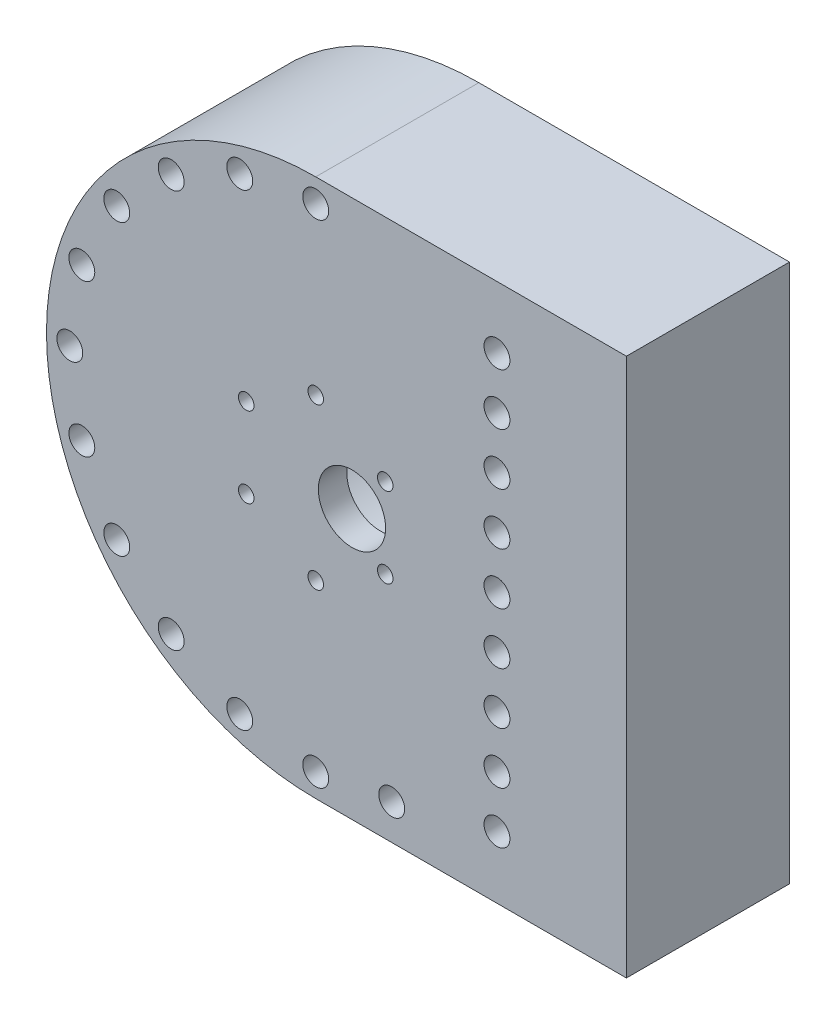
SolidWorks part; units mm, degrees
ref_plane "Alzado" through (0, 0, 0) normal (0, 0, 1) x (1, 0, 0)
ref_plane "Planta" through (0, 0, 0) normal (0, 1, 0) x (1, 0, 0)
ref_plane "Vista lateral" through (0, 0, 0) normal (1, 0, 0) x (0, 0, -1)
sketch "Croquis1" plane through (0, 0, 0) normal (0, 0, 1) x (1, 0, 0)
  line L0 (0, 52) -> (60, 52)
  line L1 (0, -52) -> (60, -52)
  line L2 (60, 52) -> (60, -52)
  arc A0 (0, 52) -> (0, -52) centre (0, 0) ccw
  circle A1 centre (0, 0) radius 18.725
  dimension "D1" = 104
  dimension "D3" = 37.45
  dimension "D2" = 60
extrude "Saliente-Extruir1" add sketch "Croquis1" along normal blind 26
sketch "Croquis2" plane through (0, 0, 26) normal (0, 0, 1) x (1, 0, 0)
  line L9 (0, -52) -> (60, -52)
  line L10 (60, -52) -> (60, 52)
  line L11 (60, 52) -> (0, 52)
  line L12 (0, -52) -> (60, -52)
  line L13 (60, -52) -> (60, 52)
  line L14 (60, 52) -> (0, 52)
  circle A0 centre (0, 0) radius 18.5 construction
  circle A3 centre (7, 0) radius 6.5
  circle A4 centre (13.4234, -7.75) radius 1.5
  circle A5 centre (13.4234, 7.75) radius 1.5
  circle A6 centre (0, 15.5) radius 1.5
  circle A7 centre (0, -15.5) radius 1.5
  circle A8 centre (-13.4234, -7.75) radius 1.5
  circle A9 centre (-13.4234, 7.75) radius 1.5
  arc A12 (0, 52) -> (0, -52) centre (0, 0) ccw
  arc A13 (0, 52) -> (0, -52) centre (0, 0) ccw
  dimension "D1" = 37
  dimension "D2" = 13
  dimension "D3" = 7
  dimension "D4" = 0
extrude "Saliente-Extruir2" add sketch "Croquis2" along normal blind 5.5
sketch "Croquis3" plane through (0, 0, 31.5) normal (0, 0, 1) x (1, 0, 0)
  line L0 (0, 0) -> (66.312, 0) construction
  line L1 (35, 40) -> (35, 20) construction
  line L2 (0, 0) -> (0, 47.5) construction
  line L3 (0, 0) -> (-14.6783, 45.1752) construction
  circle A0 centre (35, 0) radius 2.5
  circle A1 centre (35, 20) radius 2.5
  circle A2 centre (35, 40) radius 2.5
  circle A3 centre (35, -40) radius 2.5
  circle A4 centre (35, -20) radius 2.5
  circle A5 centre (0, 0) radius 47.5 construction
  circle A6 centre (-14.6783, 45.1752) radius 2.5
  circle A7 centre (-38.4283, 27.9198) radius 2.5
  circle A8 centre (-47.5, 0) radius 2.5
  circle A9 centre (-38.4283, -27.9198) radius 2.5
  circle A10 centre (-14.6783, -45.1752) radius 2.5
  circle A11 centre (14.6783, -45.1752) radius 2.5
  point P30 (0, 0)
  dimension "D1" = 5
  dimension "D4" = 95
  dimension "D6" = 5
  dimension "D2" = 35
  dimension "D5" = 18
  dimension "D3" = 3
extrude "Cortar-Extruir1" cut sketch "Croquis3" against normal through all
sketch "Croquis4" plane through (0, 0, 31.5) normal (0, 0, 1) x (1, 0, 0)
  circle A0 centre (0, 0) radius 47.5 construction
  circle A1 centre (0, 47.5) radius 2.5
  circle A2 centre (-27.9198, 38.4283) radius 2.5
  circle A3 centre (-45.1752, 14.6783) radius 2.5
  circle A4 centre (-45.1752, -14.6783) radius 2.5
  circle A5 centre (-27.9198, -38.4283) radius 2.5
  circle A6 centre (0, -47.5) radius 2.5
  circle A7 centre (35, 30) radius 2.5
  circle A8 centre (35, 10) radius 2.5
  circle A9 centre (35, -10) radius 2.5
  circle A10 centre (35, -30) radius 2.5
  point P18 (0, 0)
  dimension "D1" = 95
  dimension "D2" = 5
  dimension "D3" = 5
  dimension "D4" = 30
  dimension "D5" = 35
  dimension "D6" = 4
extrude "Cortar-Extruir2" cut sketch "Croquis4" against normal blind 20
